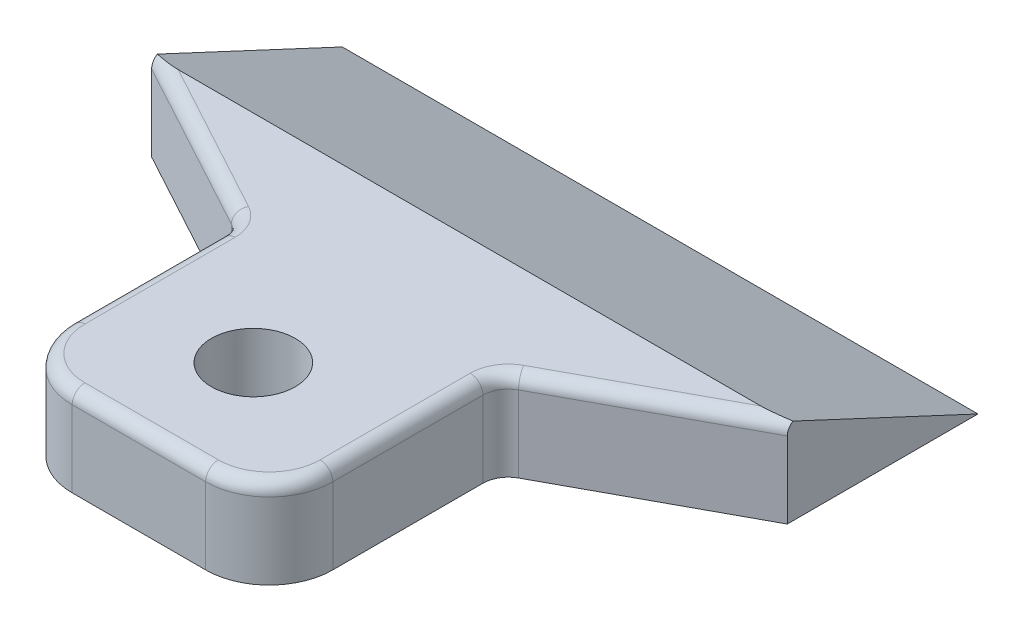
SolidWorks part; units mm, degrees
material "1.0036 (S235JRG1)"
ref_plane "Front Plane" through (0, 0, 0) normal (0, 0, 1) x (1, 0, 0)
ref_plane "Top Plane" through (0, 0, 0) normal (0, 1, 0) x (1, 0, 0)
ref_plane "Right Plane" through (0, 0, 0) normal (1, 0, 0) x (0, 0, -1)
sketch "Sketch1" plane through (0, 0, 0) normal (0, 1, 0) x (1, 0, 0)
  line L2 (10.25, 18) -> (25, 26)
  line L3 (25, 26) -> (25, 41)
  line L4 (25, 41) -> (-25, 41)
  line L6 (0, 41) -> (0, 0) construction
  line L8 (-10.25, 18) -> (-25, 26)
  line L9 (-25, 26) -> (-25, 41)
  line L10 (-10.25, 18) -> (10.25, 18) construction
  line L11 (-10.25, 18) -> (-10.25, 5)
  line L12 (-5.25, 0) -> (0, 0)
  line L13 (0, 0) -> (5.25, 0)
  line L14 (10.25, 5) -> (10.25, 18)
  circle A0 centre (0, 9) radius 3.3
  arc A7 (5.25, 0) -> (10.25, 5) centre (5.25, 5) ccw
  arc A8 (-10.25, 5) -> (-5.25, 0) centre (-5.25, 5) ccw
  dimension "D6" = 6.6
  dimension "D9" = 9
  dimension "D8" = 5
  dimension "D1" = 25
  dimension "D2" = 10.25
  dimension "D3" = 15
  dimension "D4" = 8
  dimension "D5" = 18
  dimension "D7" = 10.25
extrude "Boss-Extrude1" add sketch "Sketch1" along normal blind 7
sketch "Sketch2" plane through (25, 0, 0) normal (1, 0, 0) x (0, 0, -1)
  line L0 (0, 0) -> (26, 0) construction
  line L1 (26, 0) -> (26, 7) construction
  line L2 (26, 7) -> (41, 0)
  line L3 (41, 7) -> (41, 0) construction
  line L4 (41, 0) -> (41, 7)
  line L5 (41, 7) -> (26, 7)
  dimension "D1" = 0
extrude "Cut-Extrude1" cut sketch "Sketch2" against normal through all
sketch "Sketch4" plane through (0, 0, 0) normal (0, -1, 0) x (1, 0, 0)
  circle A0 centre (0, -9) radius 7
  dimension "D1" = 14
extrude "Cut-Extrude2" cut sketch "Sketch4" against normal blind 2
sketch "Sketch5" plane through (0, 0, 0) normal (0, -1, 0) x (1, 0, 0)
  line L0 (-25, -26) -> (25, -26)
split line "Split Line1"
fillet "Fillet1" radius 2 2 edges at (10.25, 3.5, -18) (-10.25, 3.5, -18)
sketch "Sketch6" plane through (0, 0, 0) normal (0, -1, 0) x (1, 0, 0)
  line L1 (25, -41) -> (15, -41)
  line L2 (25, -41) -> (25, -36)
  line L3 (25, -36) -> (15, -36)
  line L4 (15, -41) -> (15, -36)
  line L5 (-25, -41) -> (-15, -41)
  line L6 (-25, -41) -> (-25, -36)
  line L7 (-25, -36) -> (-15, -36)
  line L8 (-15, -41) -> (-15, -36)
  dimension "D1" = 5
  dimension "D2" = 10
  dimension "D3" = 5
  dimension "D4" = 10
split line "Split Line2"
fillet "Fillet2" radius 1 9 edges at (-18.1482, 7, -22.2838) (-10.5314, 7, -17.8325) (18.1482, 7, -22.2838) (10.5314, 7, -17.8325) (10.25, 7, -10.9048) (8.7855, 7, -1.4645) (0, 7, 0) (-8.7855, 7, -1.4645) (-10.25, 7, -10.9048)
